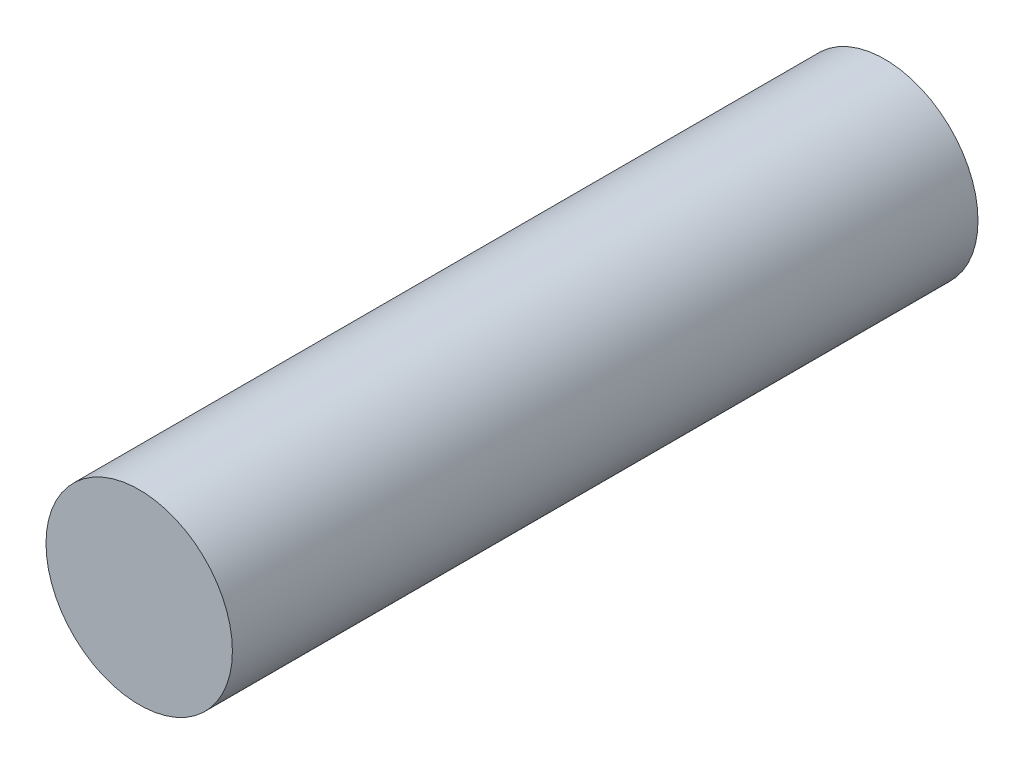
SolidWorks part; units mm, degrees
ref_plane "前视基准面" through (0, 0, 0) normal (0, 0, 1) x (1, 0, 0)
ref_plane "上视基准面" through (0, 0, 0) normal (0, 1, 0) x (1, 0, 0)
ref_plane "右视基准面" through (0, 0, 0) normal (1, 0, 0) x (0, 0, -1)
other "Configuration Table"
sketch "Profile1" plane through (0, 0, 0) normal (0, 0, 1) x (1, 0, 0)
  circle A0 centre (0, 0) radius 5
sketch "Path1" plane through (0, 0, 0) normal (1, 0, 0) x (0, 0, -1)
  line L0 (0, 0) -> (-40, 0)
sweep "sweep_merge_false" add profiles "Profile1" path "Path1"
